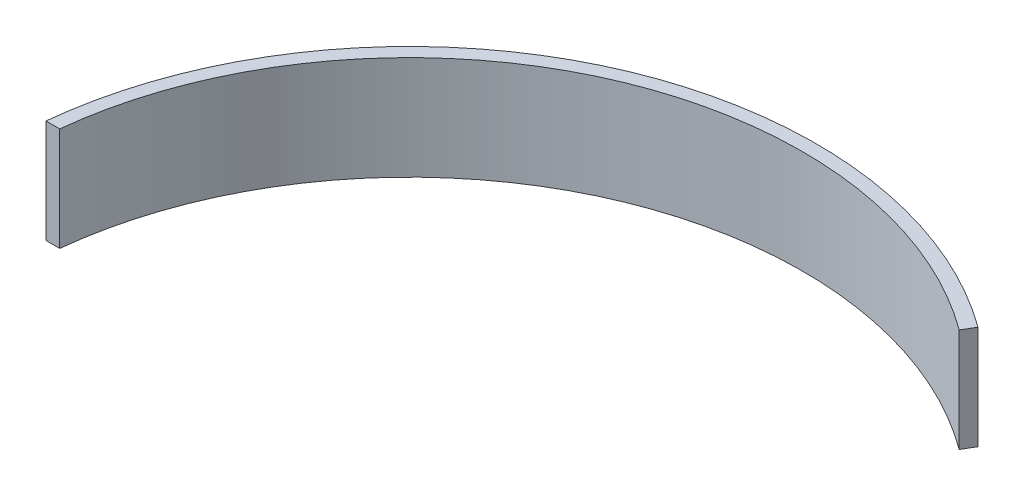
SolidWorks part; units mm, degrees
ref_plane "Front Plane" through (0, 0, 0) normal (0, 0, 1) x (1, 0, 0)
ref_plane "Top Plane" through (0, 0, 0) normal (0, 1, 0) x (1, 0, 0)
ref_plane "Right Plane" through (0, 0, 0) normal (1, 0, 0) x (0, 0, -1)
sketch "Sketch1" plane through (0, 0, 0) normal (0, 1, 0) x (1, 0, 0)
  line L0 (-156.4467, 16.1161) -> (-151.1432, 16.1161)
  line L1 (92.5691, 127.1466) -> (89.8661, 122.5891)
  arc A0 (-151.1432, 16.1161) -> (89.8661, 122.5891) centre (0, 0) cw
  arc A1 (-156.4467, 16.1161) -> (92.5691, 127.1466) centre (0, 0) cw
extrude "Boss-Extrude1" add sketch "Sketch1" along normal blind 40
